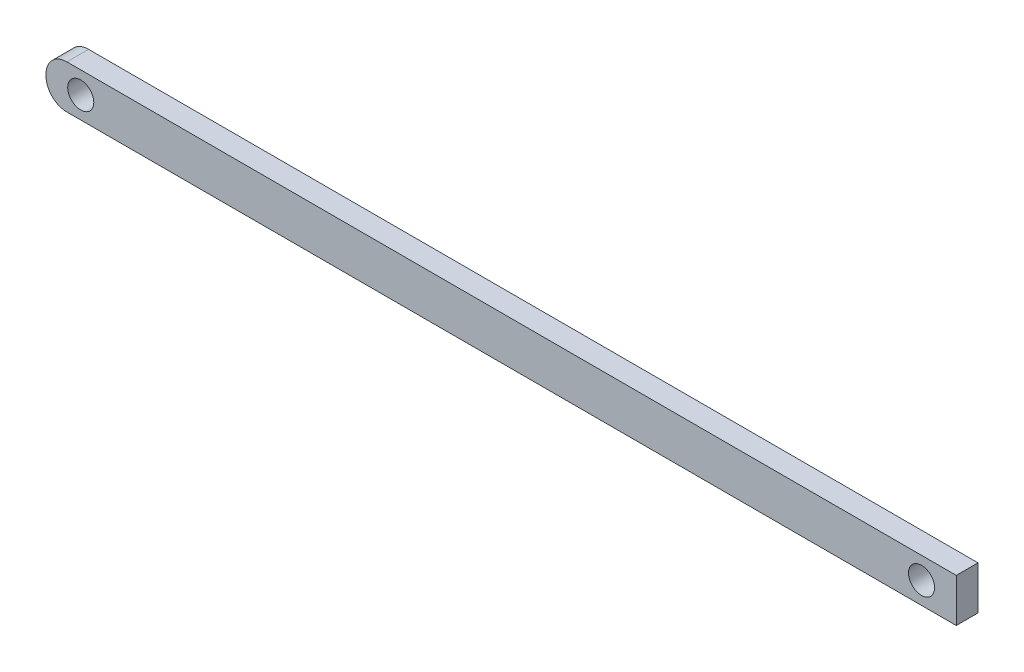
SolidWorks part; units mm, degrees
ref_plane "Front Plane" through (0, 0, 0) normal (0, 0, 1) x (1, 0, 0)
ref_plane "Top Plane" through (0, 0, 0) normal (0, 1, 0) x (1, 0, 0)
ref_plane "Right Plane" through (0, 0, 0) normal (1, 0, 0) x (0, 0, -1)
sketch "Sketch1" plane through (0, 0, 0) normal (0, 0, 1) x (1, 0, 0)
  line L0 (-366.9023, 0) -> (365.8789, 0) construction
  line L1 (0, 167.332) -> (0, -206.2227) construction
  line L3 (-250, 12.5) -> (262, 12.5)
  line L4 (-262, 0.5) -> (-262, -0.5)
  line L5 (-250, -12.5) -> (262, -12.5)
  line L6 (262, 12.5) -> (262, -12.5)
  circle A0 centre (-242, 0) radius 7.5
  circle A1 centre (242, 0) radius 7.5
  arc A2 (-262, 0.5) -> (-250, 12.5) centre (-250, 0.5) cw
  arc A3 (-262, -0.5) -> (-250, -12.5) centre (-250, -0.5) ccw
  point P5 (0, 0)
  point P16 (-262, 12.5)
  point P19 (-262, -12.5)
  dimension "D6" = 12
  dimension "D7" = 12
  dimension "D8" = 15
  dimension "D9" = 15
  dimension "D1" = 524
  dimension "D2" = 25
  dimension "D3" = 12.5
  dimension "D4" = 242
  dimension "D5" = 242
extrude "Boss-Extrude2" add sketch "Sketch1" along normal blind 25
sketch "Sketch2" plane through (262, 0, 0) normal (1, 0, 0) x (0, 0, -1)
  line L0 (-32.3025, 0) -> (15.1745, 0) construction
  line L1 (0, 13.7847) -> (0, -14.0646) construction
  line L3 (-25, 12.5) -> (0, 12.5) construction
  line L4 (0, 12.5) -> (-12.5, 12.5)
  line L5 (-12.5, 12.5) -> (-12.5, -12.5)
  line L6 (-25, -12.5) -> (0, -12.5) construction
  line L7 (-12.5, -12.5) -> (0, -12.5)
  line L8 (0, -12.5) -> (0, 12.5)
extrude "Cut-Extrude1" cut sketch "Sketch2" against normal through all both and the other way through all
